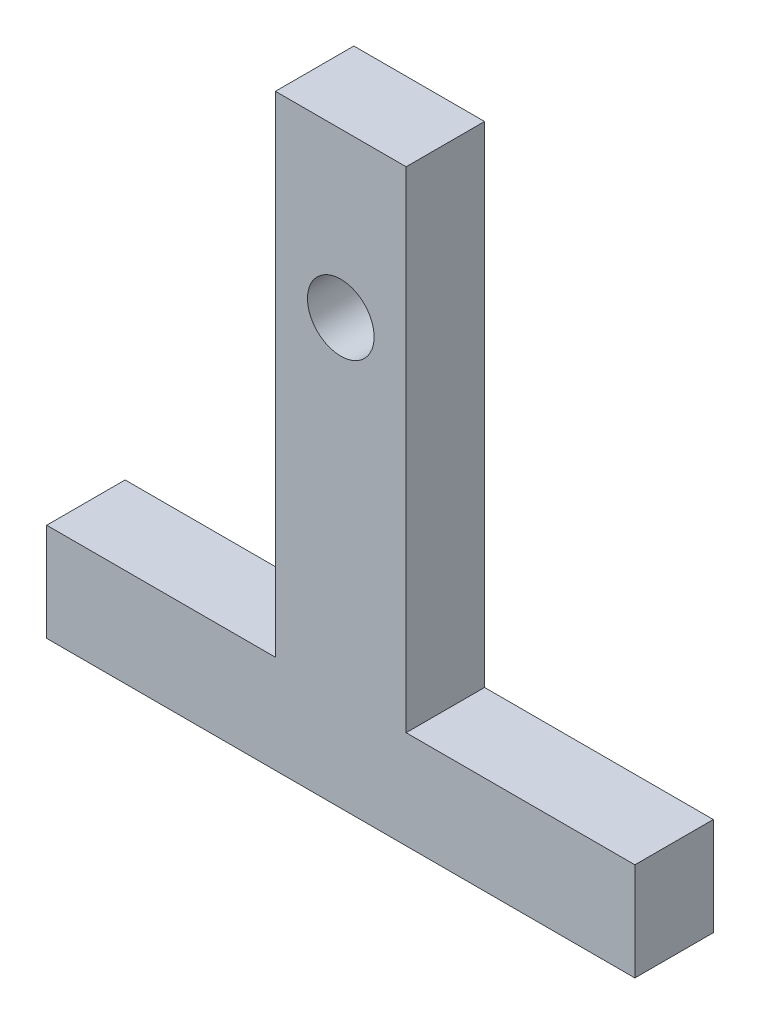
SolidWorks part; units mm, degrees
ref_plane "前视基准面" through (0, 0, 0) normal (0, 0, 1) x (1, 0, 0)
ref_plane "上视基准面" through (0, 0, 0) normal (0, 1, 0) x (1, 0, 0)
ref_plane "右视基准面" through (0, 0, 0) normal (1, 0, 0) x (0, 0, -1)
other "Configuration Table"
sketch "草图1" plane through (0, 0, 0) normal (0, 0, 1) x (1, 0, 0)
  line L0 (-45, 0) -> (45, 0)
  line L1 (45, 0) -> (45, 15)
  line L2 (45, 15) -> (10, 15)
  line L3 (10, 15) -> (10, 90)
  line L4 (10, 90) -> (-10, 90)
  line L5 (-10, 90) -> (-10, 15)
  line L6 (-10, 15) -> (-45, 15)
  line L7 (-45, 15) -> (-45, 0)
  circle A0 centre (0, 65) radius 5.1
extrude "凸台-拉伸1" add sketch "草图1" along normal blind 12
